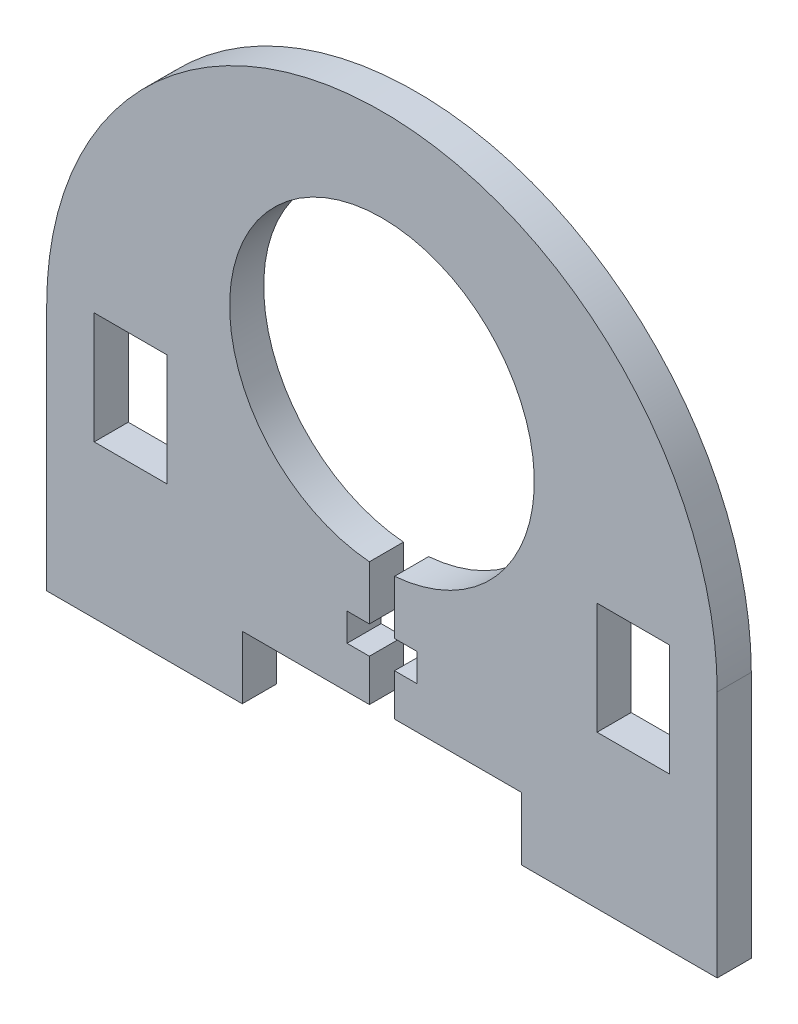
SolidWorks part; units mm, degrees
ref_plane "Front Plane" through (0, 0, 0) normal (0, 0, 1) x (1, 0, 0)
ref_plane "Top Plane" through (0, 0, 0) normal (0, 1, 0) x (1, 0, 0)
ref_plane "Right Plane" through (0, 0, 0) normal (1, 0, 0) x (0, 0, -1)
sketch "Sketch1" plane through (0, 0, 0) normal (0, 0, 1) x (1, 0, 0)
  line L0 (-30.48, 19.5049) -> (30.48, 19.5049) construction
  line L1 (30.48, -11.2601) -> (-30.48, -11.2601)
  line L2 (30.48, -11.2601) -> (30.48, 11.2601)
  line L3 (30.48, 11.2601) -> (-30.48, 11.2601) construction
  line L4 (-30.48, -11.2601) -> (-30.48, 11.2601)
  line L5 (30.48, -11.2601) -> (-30.48, 11.2601) construction
  line L6 (30.48, 11.2601) -> (-30.48, -11.2601) construction
  line L7 (0, 41.7401) -> (0, -11.2601) construction
  arc A0 (-30.48, 11.2601) -> (30.48, 11.2601) centre (0, 11.2601) cw
  circle A3 centre (0, 19.5049) radius 16.5 construction
  circle A4 centre (0, 28.5049) radius 2.5 construction
  point P0 (0, 0)
  dimension "D2" = 33
  dimension "D4" = 5
  dimension "D1" = 30.765
  dimension "D3" = 9
  dimension "D5" = 60.96
  dimension "D6" = 22.2352
extrude "Boss-Extrude1" add sketch "Sketch1" along normal blind 3.0988
sketch "Sketch2" plane through (0, 0, 3.0988) normal (0, 0, 1) x (1, 0, 0)
  circle A0 centre (0, 19.5049) radius 13.85
  dimension "D1" = 27.7
extrude "Cut-Extrude1" cut sketch "Sketch2" against normal up to next
sketch "Sketch3" plane through (0, 0, 3.0988) normal (0, 0, 1) x (1, 0, 0)
  line L0 (30.48, -11.2601) -> (-30.48, -11.2601) construction
  line L1 (-12.7, -11.2601) -> (12.7, -11.2601)
  line L2 (-12.7, -11.2601) -> (-12.7, -5.5451)
  line L3 (-12.7, -5.5451) -> (12.7, -5.5451)
  line L4 (12.7, -11.2601) -> (12.7, -5.5451)
  line L6 (0, 41.7401) -> (0, -11.2601) construction
  point P6 (0, -5.5451)
  dimension "D1" = 5.715
  dimension "D2" = 25.4
extrude "Cut-Extrude2" cut sketch "Sketch3" against normal up to next
sketch "Sketch4" plane through (0, 0, 3.0988) normal (0, 0, 1) x (1, 0, 0)
  line L0 (-30.48, -11.2601) -> (-12.7, -11.2601) construction
  line L1 (30.48, -11.2601) -> (-30.48, -11.2601) construction
  line L2 (-12.7, -5.5451) -> (-12.7, -11.2601) construction
  line L3 (-22.8266, -1014.3325) -> (-22.8266, 48985.6675) construction
  line L4 (0, -1.7043) -> (0, 1.7043) construction
  line L5 (-19.9691, 3.9799) -> (-25.6841, 3.9799)
  line L6 (-19.9691, 3.9799) -> (-19.9691, 10.3299)
  line L7 (-19.9691, 10.3299) -> (-25.6841, 10.3299)
  line L8 (-25.6841, 3.9799) -> (-25.6841, 10.3299)
  line L9 (-19.9691, 3.9799) -> (-25.6841, 10.3299) construction
  line L10 (-19.9691, 10.3299) -> (-25.6841, 3.9799) construction
  line L11 (19.9691, 1.4399) -> (25.6841, -4.9101) construction
  line L12 (-19.9691, -4.9101) -> (-25.6841, -4.9101)
  line L13 (-19.9691, -4.9101) -> (-19.9691, 1.4399)
  line L14 (-19.9691, 1.4399) -> (-25.6841, 1.4399)
  line L15 (-25.6841, -4.9101) -> (-25.6841, 1.4399)
  line L16 (-19.9691, -4.9101) -> (-25.6841, 1.4399) construction
  line L17 (-19.9691, 1.4399) -> (-25.6841, -4.9101) construction
  line L18 (19.9691, -4.9101) -> (25.6841, 1.4399) construction
  line L19 (19.9691, 10.3299) -> (25.6841, 3.9799) construction
  line L20 (19.9691, 3.9799) -> (25.6841, 10.3299) construction
  line L21 (25.6841, -4.9101) -> (25.6841, 1.4399)
  line L22 (19.9691, 1.4399) -> (25.6841, 1.4399)
  line L23 (19.9691, -4.9101) -> (19.9691, 1.4399)
  line L24 (19.9691, -4.9101) -> (25.6841, -4.9101)
  line L25 (25.6841, 3.9799) -> (25.6841, 10.3299)
  line L26 (19.9691, 10.3299) -> (25.6841, 10.3299)
  line L27 (19.9691, 3.9799) -> (19.9691, 10.3299)
  line L28 (19.9691, 3.9799) -> (25.6841, 3.9799)
  point P7 (-22.8266, -11.2601)
  point P9 (-22.8266, 7.1549)
  point P17 (-22.8266, -1.7351)
  point P23 (-21.59, -11.2601)
  point P35 (22.8266, -1.7351)
  point P36 (22.8266, 7.1549)
  dimension "D1" = 6.35
  dimension "D2" = 6.35
  dimension "D3" = 5.715
  dimension "D4" = 5.715
  dimension "D5" = 6.35
  dimension "D6" = 2.54
  dimension "D7" = 1.2366
extrude "Cut-Extrude3" [suppressed] cut sketch "Sketch4" against normal up to next
sketch "Sketch5" plane through (0, 0, 3.0988) normal (0, 0, 1) x (1, 0, 0)
  line L0 (0, 41.7401) -> (0, -11.2601) construction
  line L1 (3.175, -1.7351) -> (1.143, -1.7351)
  line L2 (3.175, -1.7351) -> (3.175, 0.8049)
  line L3 (3.175, 0.8049) -> (1.143, 0.8049)
  line L4 (-3.175, -1.7351) -> (-3.175, 0.8049)
  line L5 (3.175, -1.7351) -> (-3.175, 0.8049) construction
  line L6 (3.175, 0.8049) -> (-3.175, -1.7351) construction
  line L7 (12.7, -5.5451) -> (-12.7, -5.5451) construction
  line L8 (-1.143, 0.8049) -> (-3.175, 0.8049)
  line L9 (-1.143, -5.5451) -> (1.143, -5.5451)
  line L10 (-1.143, -5.5451) -> (-1.143, -1.7351)
  line L11 (-1.143, 8.4249) -> (1.143, 8.4249)
  line L12 (1.143, -5.5451) -> (1.143, -1.7351)
  line L13 (-1.143, 0.8049) -> (-1.143, 8.4249)
  line L14 (1.143, 0.8049) -> (1.143, 8.4249)
  line L15 (-1.143, -1.7351) -> (-3.175, -1.7351)
  point P0 (0, -0.4651)
  point P14 (0, 8.4249)
  dimension "D1" = 6.35
  dimension "D2" = 2.54
  dimension "D3" = 3.81
  dimension "D4" = 2.286
  dimension "D5" = 13.97
extrude "Cut-Extrude4" cut sketch "Sketch5" against normal up to next
sketch "Sketch6" plane through (0, 0, 3.0988) normal (0, 0, 1) x (1, 0, 0)
  line L0 (-22.86, 31.4207) -> (-22.86, -11.2601) construction
  line L1 (30.48, -11.2601) -> (-30.48, -11.2601) construction
  line L2 (0, -1.7043) -> (0, 1.7043) construction
  line L3 (22.86, 31.4207) -> (22.86, -11.2601) construction
  line L4 (-30.48, -11.2601) -> (-30.48, 11.2601) construction
  line L5 (19.558, 12.7905) -> (19.558, 2.6305)
  line L6 (-26.162, 12.7905) -> (-19.558, 12.7905)
  line L7 (-26.162, 12.7905) -> (-26.162, 2.6305)
  line L8 (-26.162, 2.6305) -> (-19.558, 2.6305)
  line L9 (-19.558, 12.7905) -> (-19.558, 2.6305)
  line L10 (26.162, 2.6305) -> (19.558, 2.6305)
  line L11 (26.162, 12.7905) -> (26.162, 2.6305)
  line L12 (26.162, 12.7905) -> (19.558, 12.7905)
  arc A0 (30.48, 11.2601) -> (-30.48, 11.2601) centre (0, 11.2601) ccw construction
  point P17 (-22.86, 12.7905)
  dimension "D1" = 7.62
  dimension "D2" = 6.604
  dimension "D3" = 24.0505
  dimension "D4" = 10.16
extrude "Cut-Extrude5" cut sketch "Sketch6" against normal up to next
equation "\"D2@Sketch1\"=33mm"
equation "\"D1@Sketch1\"=0.75+\"motor offset\"+\"thickness0.25\""
equation "\"t\"=0.225"
equation "\"D1@Boss-Extrude1\"=\"thickness0.125\""
equation "\"D1@Sketch3\"=\"thickness0.25\""
equation "\"D4@Sketch4\"=\"t\""
equation "\"D3@Sketch4\"=\"t\""
equation "\"motor offset\"= 6mm"
equation "\"thickness0.25\"= 0.225in"
equation "\"thickness0.125\"= 0.122in"
